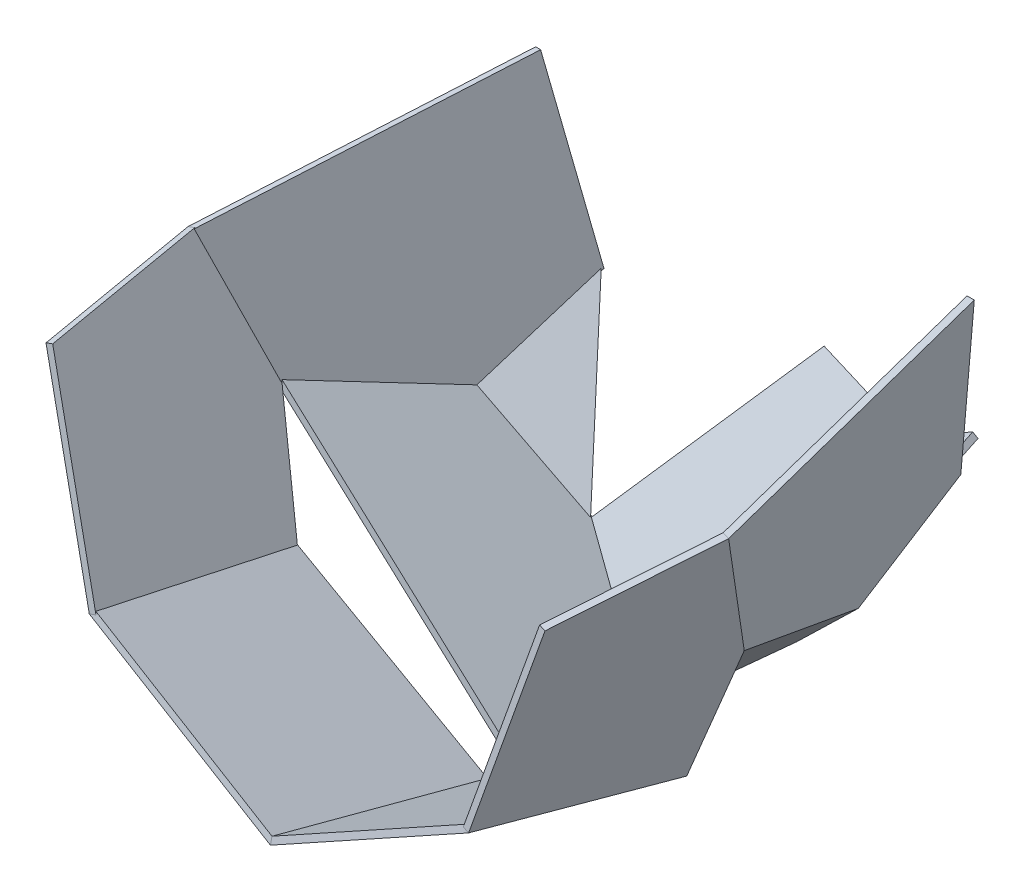
SolidWorks part; units mm, degrees
ref_plane "Front Plane" through (0, 0, 0) normal (1, 0, 0) x (0, 1, 0)
ref_plane "Top Plane" through (0, 0, 0) normal (0, 0, 1) x (0, 1, 0)
ref_plane "Right Plane" through (0, 0, 0) normal (0, 1, 0) x (-1, 0, 0)
sketch3d "3DSketch1"
  line L0 (0, -2.8671, -39.258) -> (32.988, 25.4939, -55.3338)
  line L1 (32.988, 25.4939, -55.3338) -> (24.5648, 44.0621, -121.0095)
  line L2 (24.5648, 44.0621, -121.0095) -> (0, 28.6181, -124.3821)
  line L3 (0, 28.6181, -124.3821) -> (0, -2.8671, -39.258)
  line L4 (0, 3.2239, 1.468) -> (0, -2.8671, -39.258)
  line L7 (61.1453, 53.062, -46.5876) -> (32.988, 25.4939, -55.3338)
  line L8 (61.1453, 53.062, -46.5876) -> (57.1657, 69.5552, -82.9606)
  line L9 (57.1657, 69.5552, -82.9606) -> (24.5648, 44.0621, -121.0095)
  line L10 (32.988, 25.4939, -55.3338) -> (57.1657, 69.5552, -82.9606)
  line L11 (57.1657, 69.5552, -82.9606) -> (69.3295, 127.3358, -75.0686)
  line L12 (69.3295, 127.3358, -75.0686) -> (85.4412, 116.9517, 18.7033)
  line L13 (0, 3.2239, 1.468) -> (74.1539, 72.5316, 2.4728)
  line L14 (74.1539, 72.5316, 2.4728) -> (61.1453, 53.062, -46.5876)
  line L15 (0, 1.7957, 9.973) -> (62.5527, 35.6802, 9.0563)
  line L16 (62.5527, 35.6802, 9.0563) -> (74.1539, 72.5316, 2.4728)
  line L17 (0, 1.7957, 9.973) -> (0, 20.0063, 78.114)
  line L18 (0, 20.0063, 78.114) -> (59.96, 52.0015, 75.4214)
  line L19 (59.96, 52.0015, 75.4214) -> (78.8698, 114.1507, 70.1912)
  line L20 (78.8698, 114.1507, 70.1912) -> (85.4412, 116.9517, 18.7033)
  line L21 (74.1539, 72.5316, 2.4728) -> (85.4412, 116.9517, 18.7033)
  line L22 (59.96, 52.0015, 75.4214) -> (62.5527, 35.6802, 9.0563)
  line L23 (-59.96, 52.0015, 75.4214) -> (-62.5527, 35.6802, 9.0563)
  line L24 (-74.1539, 72.5316, 2.4728) -> (-85.4412, 116.9517, 18.7033)
  line L25 (-78.8698, 114.1507, 70.1912) -> (-85.4412, 116.9517, 18.7033)
  line L26 (-59.96, 52.0015, 75.4214) -> (-78.8698, 114.1507, 70.1912)
  line L27 (0, 20.0063, 78.114) -> (-59.96, 52.0015, 75.4214)
  line L28 (-62.5527, 35.6802, 9.0563) -> (-74.1539, 72.5316, 2.4728)
  line L29 (0, 1.7957, 9.973) -> (-62.5527, 35.6802, 9.0563)
  line L30 (-74.1539, 72.5316, 2.4728) -> (-61.1453, 53.062, -46.5876)
  line L31 (0, 3.2239, 1.468) -> (-74.1539, 72.5316, 2.4728)
  line L32 (-69.3295, 127.3358, -75.0686) -> (-85.4412, 116.9517, 18.7033)
  line L33 (-57.1657, 69.5552, -82.9606) -> (-69.3295, 127.3358, -75.0686)
  line L34 (-32.988, 25.4939, -55.3338) -> (-57.1657, 69.5552, -82.9606)
  line L35 (-57.1657, 69.5552, -82.9606) -> (-24.5648, 44.0621, -121.0095)
  line L36 (-61.1453, 53.062, -46.5876) -> (-57.1657, 69.5552, -82.9606)
  line L37 (-61.1453, 53.062, -46.5876) -> (-32.988, 25.4939, -55.3338)
  line L38 (-24.5648, 44.0621, -121.0095) -> (0, 28.6181, -124.3821)
  line L39 (-32.988, 25.4939, -55.3338) -> (-24.5648, 44.0621, -121.0095)
  line L40 (0, -2.8671, -39.258) -> (-32.988, 25.4939, -55.3338)
  point P0 (0, -2.8671, -39.258)
  point P1 (0, 3.2239, 1.468)
  point P3 (0, 1.7957, 9.973)
  point P5 (0, 20.0063, 78.114)
  point P7 (59.96, 52.0015, 75.4214)
  point P9 (62.5527, 35.6802, 9.0563)
  point P11 (74.1539, 72.5316, 2.4728)
  point P13 (61.1453, 53.062, -46.5876)
  point P15 (32.988, 25.4939, -55.3338)
  point P17 (57.1657, 69.5552, -82.9606)
  point P19 (69.3295, 127.3358, -75.0686)
  point P21 (85.4412, 116.9517, 18.7033)
  point P23 (78.8698, 114.1507, 70.1912)
  point P25 (0, 28.6181, -124.3821)
  point P27 (24.5648, 44.0621, -121.0095)
  point P28 (0, 0, 0)
ref_plane "Plane1" through (-0.3466, -0.6352, 0.1697) normal (0.4663, 0.8546, -0.2284) x (0.8846, -0.4505, 0.1204)
sketch "Sketch3" plane through (-0.3466, -0.6352, 0.1697) normal (0.4663, 0.8546, -0.2284) x (0.8846, -0.4505, 0.1204)
  line L0 (-67.3882, -86.2904) -> (0.3918, -80.6309)
  line L1 (0.3918, -80.6309) -> (0.3918, -10.0985)
  line L2 (0.3918, -10.0985) -> (-70.319, -17.9614)
  line L3 (-70.319, -17.9614) -> (-67.3882, -86.2904)
ref_plane "Plane2" through (-48.2463, -14.2266, 5.3836) normal (-0.9537, -0.2812, 0.1064) x (0.1021, 0.0301, 0.9943)
sketch "Sketch4" plane through (-48.2463, -14.2266, 5.3836) normal (-0.9537, -0.2812, 0.1064) x (0.1021, 0.0301, 0.9943)
  line L0 (65.1777, 131.7969) -> (70.4378, 66.837)
  line L1 (70.4378, 66.837) -> (3.6936, 51.9154)
  line L2 (3.6936, 51.9154) -> (-2.9274, 90.5433)
  line L3 (-2.9274, 90.5433) -> (13.3957, 136.3422)
  line L4 (13.3957, 136.3422) -> (65.1777, 131.7969)
ref_plane "Plane3" through (-56.3545, -10.3626, -10.8302) normal (0.9664, 0.1777, 0.1857) x (0.1827, 0.0336, -0.9826)
sketch "Sketch5" plane through (-56.3545, -10.3626, -10.8302) normal (0.9664, 0.1777, 0.1857) x (0.1827, 0.0336, -0.9826)
  line L0 (-30.0564, 130.4754) -> (-13.5386, 84.7464)
  line L1 (-13.5386, 84.7464) -> (36.3905, 63.2452)
  line L2 (36.3905, 63.2452) -> (73.4115, 78.7468)
  line L3 (73.4115, 78.7468) -> (65.3758, 137.7744)
  line L4 (65.3758, 137.7744) -> (-30.0564, 130.4754)
  point P4 (73.4294, 78.7635)
ref_plane "Plane4" through (1.4808, 1.5878, -0.2375) normal (-0.678, -0.727, 0.1087) x (-0.7351, 0.6705, -0.1003)
sketch "Sketch6" plane through (1.4808, 1.5878, -0.2375) normal (-0.678, -0.727, 0.1087) x (-0.7351, 0.6705, -0.1003)
  line L0 (102.8952, -13.1742) -> (85.198, 38.2264)
  line L1 (85.198, 38.2264) -> (46.8922, 50.9542)
  line L2 (46.8922, 50.9542) -> (2.0145, 39.2502)
  line L3 (2.0145, 39.2502) -> (2.0145, -1.9288)
  line L4 (2.0145, -1.9288) -> (102.8952, -13.1742)
ref_plane "Plane5" through (-19.4, -16.7339, -9.7105) normal (0.7081, 0.6108, 0.3544) x (0.2684, 0.2315, -0.9351)
sketch "Sketch7" plane through (-19.4, -16.7339, -9.7105) normal (0.7081, 0.6108, 0.3544) x (0.2684, 0.2315, -0.9351)
  line L0 (78.335, 90.007) -> (39.4371, 80.1173)
  line L1 (39.4371, 80.1173) -> (48.7904, 40.8509)
  line L2 (48.7904, 40.8509) -> (78.335, 90.007)
ref_plane "Plane6" through (-19.1103, -14.6137, -6.5827) normal (-0.7662, -0.5859, -0.2639) x (-0.2096, -0.1603, 0.9645)
sketch "Sketch8" plane through (-19.1103, -14.6137, -6.5827) normal (-0.7662, -0.5859, -0.2639) x (-0.2096, -0.1603, 0.9645)
  line L0 (-79.1854, 89.9771) -> (-50.5431, 40.2898)
  line L1 (-50.5431, 40.2898) -> (-118.633, 49.923)
  line L2 (-118.633, 49.923) -> (-79.1854, 89.9771)
ref_plane "Plane7" through (-7.3911, -10.8774, -4.0233) normal (-0.5374, -0.7909, -0.2925) x (-0.8433, 0.5041, 0.1864)
sketch "Sketch9" plane through (-7.3911, -10.8774, -4.0233) normal (-0.5374, -0.7909, -0.2925) x (-0.8433, 0.5041, 0.1864)
  line L0 (20.3647, 128.7802) -> (30.3531, 60.7415)
  line L1 (30.3531, 60.7415) -> (-8.7644, 35.8254)
  line L2 (-8.7644, 35.8254) -> (-8.7644, 126.5857)
  line L3 (-8.7644, 126.5857) -> (20.3647, 128.7802)
extrude "Boss-Extrude1" add sketch "Sketch3" along normal blind 2
extrude "Boss-Extrude2" add sketch "Sketch5" along normal blind 2 separate body
extrude "Boss-Extrude3" add sketch "Sketch4" against normal blind 2
extrude "Boss-Extrude4" add sketch "Sketch6" against normal blind 2
extrude "Boss-Extrude5" add sketch "Sketch7" along normal blind 2
extrude "Boss-Extrude11" add sketch "Sketch9" against normal blind 2 separate body
mirror "Mirror1" about plane through (0, 0, 0) normal (1, 0, 0) of bodies 131 132
